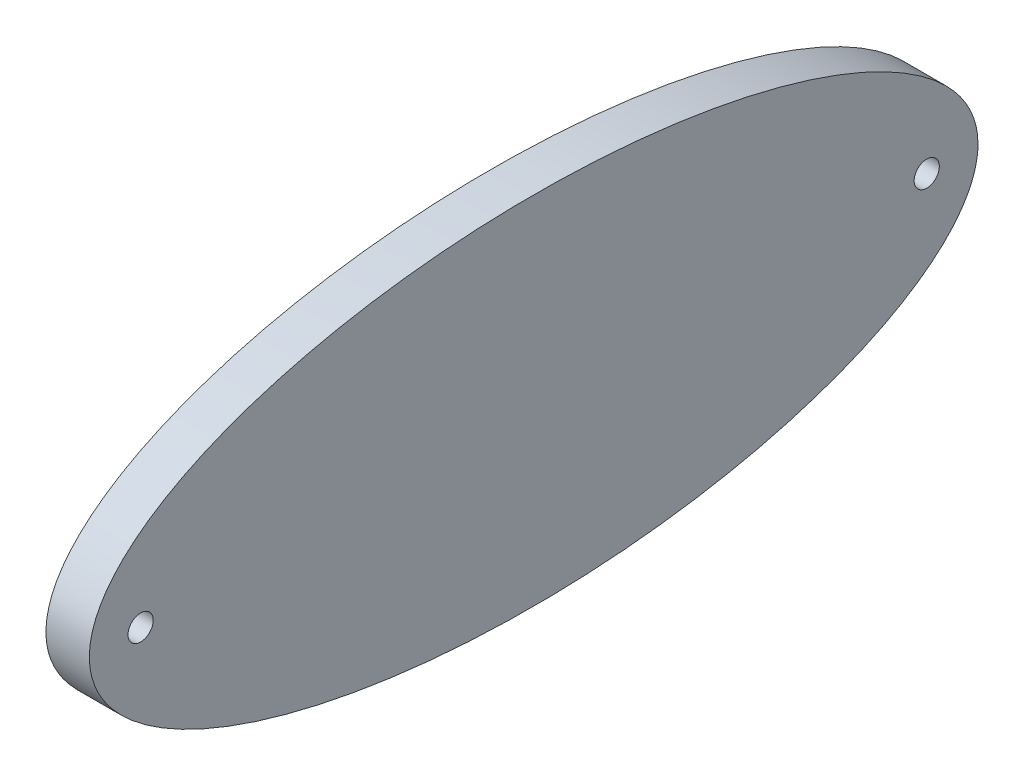
SolidWorks part; units mm, degrees
ref_plane "Front Plane" through (0, 0, 0) normal (0, 0, 1) x (1, 0, 0)
ref_plane "Top Plane" through (0, 0, 0) normal (0, 1, 0) x (1, 0, 0)
ref_plane "Right Plane" through (0, 0, 0) normal (1, 0, 0) x (0, 0, -1)
sketch "Sketch1" plane through (0, 0, 0) normal (1, 0, 0) x (0, 0, -1)
  circle A0 centre (-46, 0) radius 1.4732
  circle A1 centre (46, 0) radius 1.4732
  ellipse E0 centre (0, 0) end of major axis (52, 0) minor radius 20.85
  dimension "D3" = 2.9464
  dimension "D4" = 2.9464
  dimension "D1" = 41.7
  dimension "D2" = 104
  dimension "D5" = 6
  dimension "D6" = 6
extrude "Boss-Extrude1" add sketch "Sketch1" along normal blind 5.08
